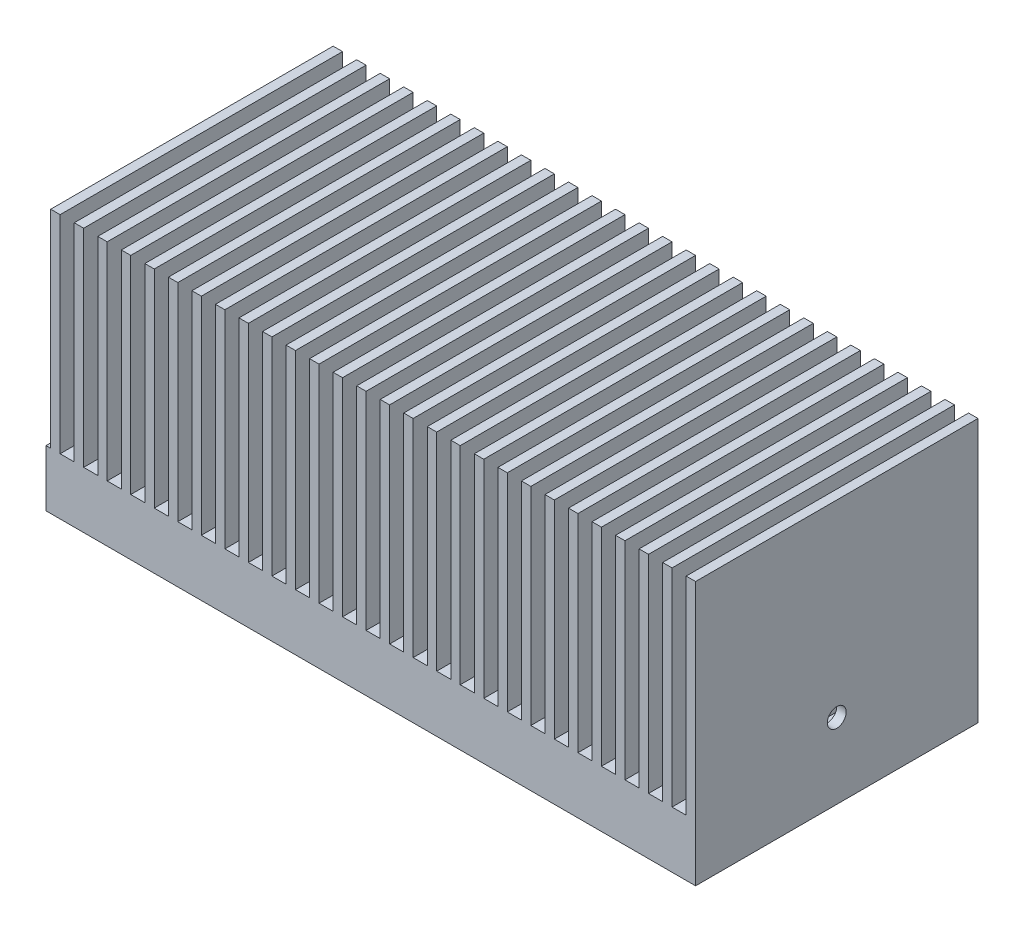
SolidWorks part; units mm, degrees
ref_plane "前视基准面" through (0, 0, 0) normal (0, 0, 1) x (1, 0, 0)
ref_plane "上视基准面" through (0, 0, 0) normal (0, 1, 0) x (1, 0, 0)
ref_plane "右视基准面" through (0, 0, 0) normal (1, 0, 0) x (0, 0, -1)
sketch "草图1" plane through (0, 0, 0) normal (0, 1, 0) x (1, 0, 0)
  line L0 (-38.2837, 0) -> (40.4297, 0) construction
  line L1 (-34.5, 15) -> (34.5, 15)
  line L2 (-34.5, 15) -> (-34.5, -15)
  line L3 (-34.5, -15) -> (34.5, -15)
  line L4 (34.5, 15) -> (34.5, -15)
  line L5 (0, 27.2258) -> (0, -28.9127) construction
  dimension "D1" = 69
  dimension "D2" = 30
extrude "拉伸1" add sketch "草图1" along normal blind 28
sketch "草图2" plane through (0, 28, 0) normal (0, 1, 0) x (-1, 0, 0)
  line L0 (1, -20.8895) -> (1, 19.2743) construction
  line L1 (-34.5, -15) -> (34.5, -15) construction
  line L2 (-1, -15) -> (0.5, -15)
  line L3 (-1, -15) -> (-1, 15)
  line L4 (-1, 15) -> (0.5, 15)
  line L5 (0.5, -15) -> (0.5, 15)
  line L6 (34.5, 15) -> (-34.5, 15) construction
  line L7 (1.5, -15) -> (3, -15)
  line L8 (1.5, -15) -> (1.5, 15)
  line L9 (1.5, 15) -> (3, 15)
  line L10 (3, -15) -> (3, 15)
  line L11 (4, -15) -> (5.5, -15)
  line L12 (4, -15) -> (4, 15)
  line L13 (4, 15) -> (5.5, 15)
  line L14 (5.5, -15) -> (5.5, 15)
  line L15 (6.5, -15) -> (8, -15)
  line L16 (6.5, -15) -> (6.5, 15)
  line L17 (6.5, 15) -> (8, 15)
  line L18 (8, -15) -> (8, 15)
  line L19 (9, -15) -> (10.5, -15)
  line L20 (9, -15) -> (9, 15)
  line L21 (9, 15) -> (10.5, 15)
  line L22 (10.5, -15) -> (10.5, 15)
  line L23 (11.5, -15) -> (13, -15)
  line L24 (11.5, -15) -> (11.5, 15)
  line L25 (11.5, 15) -> (13, 15)
  line L26 (13, -15) -> (13, 15)
  line L27 (14, -15) -> (15.5, -15)
  line L28 (14, -15) -> (14, 15)
  line L29 (14, 15) -> (15.5, 15)
  line L30 (15.5, -15) -> (15.5, 15)
  line L31 (16.5, -15) -> (18, -15)
  line L32 (16.5, -15) -> (16.5, 15)
  line L33 (16.5, 15) -> (18, 15)
  line L34 (18, -15) -> (18, 15)
  line L35 (19, -15) -> (20.5, -15)
  line L36 (19, -15) -> (19, 15)
  line L37 (19, 15) -> (20.5, 15)
  line L38 (20.5, -15) -> (20.5, 15)
  line L39 (21.5, -15) -> (23, -15)
  line L40 (21.5, -15) -> (21.5, 15)
  line L41 (21.5, 15) -> (23, 15)
  line L42 (23, -15) -> (23, 15)
  line L43 (24, -15) -> (25.5, -15)
  line L44 (24, -15) -> (24, 15)
  line L45 (24, 15) -> (25.5, 15)
  line L46 (25.5, -15) -> (25.5, 15)
  line L47 (26.5, -15) -> (28, -15)
  line L48 (26.5, -15) -> (26.5, 15)
  line L49 (26.5, 15) -> (28, 15)
  line L50 (28, -15) -> (28, 15)
  line L51 (29, -15) -> (30.5, -15)
  line L52 (29, -15) -> (29, 15)
  line L53 (29, 15) -> (30.5, 15)
  line L54 (30.5, -15) -> (30.5, 15)
  line L55 (31.5, -15) -> (33, -15)
  line L56 (31.5, -15) -> (31.5, 15)
  line L57 (31.5, 15) -> (33, 15)
  line L58 (33, -15) -> (33, 15)
  line L59 (34, -15) -> (35.5, -15)
  line L60 (34, -15) -> (34, 15)
  line L61 (34, 15) -> (35.5, 15)
  line L62 (35.5, -15) -> (35.5, 15)
  line L63 (-3.5, -15) -> (-2, -15)
  line L64 (-3.5, -15) -> (-3.5, 15)
  line L65 (-3.5, 15) -> (-2, 15)
  line L66 (-2, -15) -> (-2, 15)
  line L67 (-6, -15) -> (-4.5, -15)
  line L68 (-6, -15) -> (-6, 15)
  line L69 (-6, 15) -> (-4.5, 15)
  line L70 (-4.5, -15) -> (-4.5, 15)
  line L71 (-8.5, -15) -> (-7, -15)
  line L72 (-8.5, -15) -> (-8.5, 15)
  line L73 (-8.5, 15) -> (-7, 15)
  line L74 (-7, -15) -> (-7, 15)
  line L75 (-11, -15) -> (-9.5, -15)
  line L76 (-11, -15) -> (-11, 15)
  line L77 (-11, 15) -> (-9.5, 15)
  line L78 (-9.5, -15) -> (-9.5, 15)
  line L79 (-13.5, -15) -> (-12, -15)
  line L80 (-13.5, -15) -> (-13.5, 15)
  line L81 (-13.5, 15) -> (-12, 15)
  line L82 (-12, -15) -> (-12, 15)
  line L83 (-16, -15) -> (-14.5, -15)
  line L84 (-16, -15) -> (-16, 15)
  line L85 (-16, 15) -> (-14.5, 15)
  line L86 (-14.5, -15) -> (-14.5, 15)
  line L87 (-18.5, -15) -> (-17, -15)
  line L88 (-18.5, -15) -> (-18.5, 15)
  line L89 (-18.5, 15) -> (-17, 15)
  line L90 (-17, -15) -> (-17, 15)
  line L91 (-21, -15) -> (-19.5, -15)
  line L92 (-21, -15) -> (-21, 15)
  line L93 (-21, 15) -> (-19.5, 15)
  line L94 (-19.5, -15) -> (-19.5, 15)
  line L95 (-23.5, -15) -> (-22, -15)
  line L96 (-23.5, -15) -> (-23.5, 15)
  line L97 (-23.5, 15) -> (-22, 15)
  line L98 (-22, -15) -> (-22, 15)
  line L99 (-26, -15) -> (-24.5, -15)
  line L100 (-26, -15) -> (-26, 15)
  line L101 (-26, 15) -> (-24.5, 15)
  line L102 (-24.5, -15) -> (-24.5, 15)
  line L103 (-28.5, -15) -> (-27, -15)
  line L104 (-28.5, -15) -> (-28.5, 15)
  line L105 (-28.5, 15) -> (-27, 15)
  line L106 (-27, -15) -> (-27, 15)
  line L107 (-31, -15) -> (-29.5, -15)
  line L108 (-31, -15) -> (-31, 15)
  line L109 (-31, 15) -> (-29.5, 15)
  line L110 (-29.5, -15) -> (-29.5, 15)
  line L111 (-33.5, -15) -> (-32, -15)
  line L112 (-33.5, -15) -> (-33.5, 15)
  line L113 (-33.5, 15) -> (-32, 15)
  line L114 (-32, -15) -> (-32, 15)
  dimension "D1" = 1.5
  dimension "D2" = 0.5
  dimension "D3" = 1
extrude "切除-拉伸1" cut sketch "草图2" against normal offset from surface (22 mm away) 6 up to face at (0, 0, 0)
sketch "草图3" plane through (-34, 0, 0) normal (-1, 0, 0) x (0, 0, 1)
  line L0 (0, -2.6217) -> (0, 30.0974) construction
  line L1 (-15, 6) -> (15, 6) construction
  circle A0 centre (0, 8) radius 1
  dimension "D1" = 2
  dimension "D2" = 2
extrude "切除-拉伸2" cut sketch "草图3" against normal blind 5
sketch "草图4" plane through (34.5, 0, 0) normal (1, 0, 0) x (0, 0, -1)
  line L0 (0, -4.4989) -> (0, 30.9888) construction
  circle A0 centre (0, 8) radius 1 construction
  circle A1 centre (0, 8) radius 1
extrude "切除-拉伸3" cut sketch "草图4" against normal blind 5
